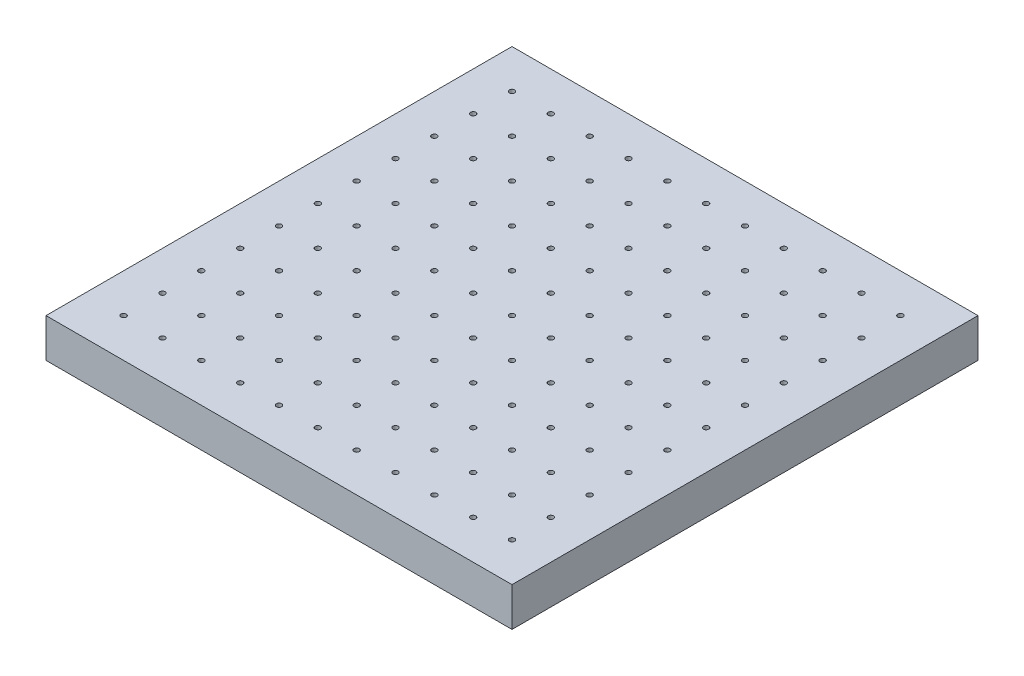
SolidWorks part; units mm, degrees
ref_plane "Front Plane" through (0, 0, 0) normal (0, 0, 1) x (1, 0, 0)
ref_plane "Top Plane" through (0, 0, 0) normal (0, 1, 0) x (1, 0, 0)
ref_plane "Right Plane" through (0, 0, 0) normal (1, 0, 0) x (0, 0, -1)
sketch "Sketch2" plane through (0, 0, 0) normal (0, 1, 0) x (1, 0, 0)
  line L1 (0, 0) -> (304.8, 0)
  line L2 (0, 0) -> (0, 304.8)
  line L3 (0, 304.8) -> (304.8, 304.8)
  line L4 (304.8, 0) -> (304.8, 304.8)
  dimension "D1" = 304.8
  dimension "D2" = 304.8
extrude "Boss-Extrude1" add sketch "Sketch2" along normal blind 25.4
hole_wizard "#8-32 Tapped Hole1" positions "Sketch8" profile "Sketch6" tap size "#8-32" standard "ANSI Inch"
sketch "Sketch8" plane through (0, 25.4, 0) normal (0, 1, 0) x (1, 0, 0)
  line L0 (0, 0) -> (304.8, 0) construction
  line L1 (0, 304.8) -> (0, 0) construction
  point P0 (25.4, 25.4)
  point P20 (50.8, 25.4)
  point P21 (76.2, 25.4)
  point P22 (101.6, 25.4)
  point P23 (127, 25.4)
  point P24 (152.4, 25.4)
  point P25 (177.8, 25.4)
  point P26 (203.2, 25.4)
  point P27 (228.6, 25.4)
  point P28 (254, 25.4)
  point P29 (279.4, 25.4)
  point P30 (50.8, 50.8)
  point P31 (76.2, 50.8)
  point P32 (101.6, 50.8)
  point P33 (127, 50.8)
  point P34 (152.4, 50.8)
  point P35 (177.8, 50.8)
  point P36 (203.2, 50.8)
  point P37 (228.6, 50.8)
  point P38 (254, 50.8)
  point P39 (279.4, 50.8)
  point P40 (50.8, 76.2)
  point P41 (76.2, 76.2)
  point P42 (101.6, 76.2)
  point P43 (127, 76.2)
  point P44 (152.4, 76.2)
  point P45 (177.8, 76.2)
  point P46 (203.2, 76.2)
  point P47 (228.6, 76.2)
  point P48 (254, 76.2)
  point P49 (279.4, 76.2)
  point P50 (50.8, 101.6)
  point P51 (76.2, 101.6)
  point P52 (101.6, 101.6)
  point P53 (127, 101.6)
  point P54 (152.4, 101.6)
  point P55 (177.8, 101.6)
  point P56 (203.2, 101.6)
  point P57 (228.6, 101.6)
  point P58 (254, 101.6)
  point P59 (279.4, 101.6)
  point P60 (50.8, 127)
  point P61 (76.2, 127)
  point P62 (101.6, 127)
  point P63 (127, 127)
  point P64 (152.4, 127)
  point P65 (177.8, 127)
  point P66 (203.2, 127)
  point P67 (228.6, 127)
  point P68 (254, 127)
  point P69 (279.4, 127)
  point P70 (50.8, 152.4)
  point P71 (76.2, 152.4)
  point P72 (101.6, 152.4)
  point P73 (127, 152.4)
  point P74 (152.4, 152.4)
  point P75 (177.8, 152.4)
  point P76 (203.2, 152.4)
  point P77 (228.6, 152.4)
  point P78 (254, 152.4)
  point P79 (279.4, 152.4)
  point P80 (50.8, 177.8)
  point P81 (76.2, 177.8)
  point P82 (101.6, 177.8)
  point P83 (127, 177.8)
  point P84 (152.4, 177.8)
  point P85 (177.8, 177.8)
  point P86 (203.2, 177.8)
  point P87 (228.6, 177.8)
  point P88 (254, 177.8)
  point P89 (279.4, 177.8)
  point P90 (50.8, 203.2)
  point P91 (76.2, 203.2)
  point P92 (101.6, 203.2)
  point P93 (127, 203.2)
  point P94 (152.4, 203.2)
  point P95 (177.8, 203.2)
  point P96 (203.2, 203.2)
  point P97 (228.6, 203.2)
  point P98 (254, 203.2)
  point P99 (279.4, 203.2)
  point P100 (50.8, 228.6)
  point P101 (76.2, 228.6)
  point P102 (101.6, 228.6)
  point P103 (127, 228.6)
  point P104 (152.4, 228.6)
  point P105 (177.8, 228.6)
  point P106 (203.2, 228.6)
  point P107 (228.6, 228.6)
  point P108 (254, 228.6)
  point P109 (279.4, 228.6)
  point P110 (50.8, 254)
  point P111 (76.2, 254)
  point P112 (101.6, 254)
  point P113 (127, 254)
  point P114 (152.4, 254)
  point P115 (177.8, 254)
  point P116 (203.2, 254)
  point P117 (228.6, 254)
  point P118 (254, 254)
  point P119 (279.4, 254)
  point P120 (50.8, 279.4)
  point P121 (76.2, 279.4)
  point P122 (101.6, 279.4)
  point P123 (127, 279.4)
  point P124 (152.4, 279.4)
  point P125 (177.8, 279.4)
  point P126 (203.2, 279.4)
  point P127 (228.6, 279.4)
  point P128 (254, 279.4)
  point P129 (279.4, 279.4)
  point P130 (25.4, 50.8)
  point P131 (25.4, 76.2)
  point P132 (25.4, 101.6)
  point P133 (25.4, 127)
  point P134 (25.4, 152.4)
  point P135 (25.4, 177.8)
  point P136 (25.4, 203.2)
  point P137 (25.4, 228.6)
  point P138 (25.4, 254)
  point P139 (25.4, 279.4)
  dimension "D1" = 25.4
  dimension "D2" = 25.4
  dimension "D3" = 11
  dimension "D4" = 11
sketch "Sketch6" plane through (25.4, 25.4, -25.4) normal (1, 0, 0) x (0, 0, 1)
  line L0 (0, 0) -> (0, 11.7058)
  line L1 (0, 11.7058) -> (1.7272, 10.668)
  line L2 (1.7272, 10.668) -> (1.7272, 0)
  line L5 (1.7272, 0) -> (0, 0)
  line L10 (0, 11.7058) -> (-1.7272, 10.668) construction
  line L11 (0, -6.35) -> (0, 107.95) construction
  dimension "Tap Drill Dia." = 3.4544
  dimension "Tap Drill Depth" = 10.668
  dimension "Drill Angle" = 118
